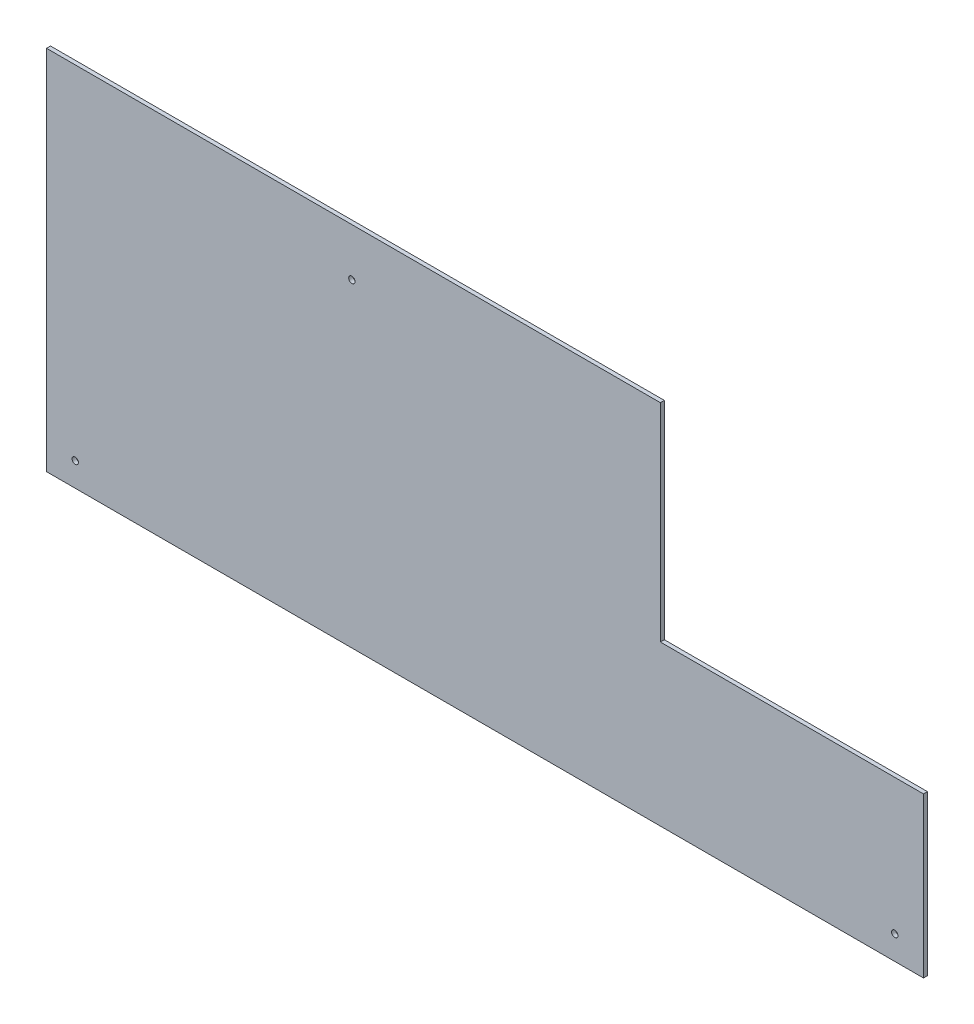
SolidWorks part; units mm, degrees
material "Acrilico (impatto medio-alto)"
ref_plane "Piano frontale" through (0, 0, 0) normal (0, 0, 1) x (1, 0, 0)
ref_plane "Piano superiore" through (0, 0, 0) normal (0, 1, 0) x (1, 0, 0)
ref_plane "Piano destro" through (0, 0, 0) normal (1, 0, 0) x (0, 0, -1)
sketch "Schizzo1" plane through (0, 0, 0) normal (0, 0, 1) x (1, 0, 0)
  line L1 (275, -115) -> (-275, -115)
  line L2 (275, -115) -> (275, 115)
  line L3 (275, 115) -> (-275, 115)
  line L4 (-275, -115) -> (-275, 115)
  line L5 (275, -115) -> (-275, 115) construction
  line L6 (275, 115) -> (-275, -115) construction
  point P4 (0, 0)
  dimension "D1" = 230
  dimension "D2" = 550
extrude "Estrusione-Estrusione1" add sketch "Schizzo1" along normal blind 2.5
sketch "Schizzo2" plane through (0, 0, 0) normal (0, 0, -1) x (-1, 0, 0)
  line L1 (-275, 115) -> (-110, 115)
  line L2 (-275, 115) -> (-275, -15)
  line L3 (-275, -15) -> (-110, -15)
  line L4 (-110, 115) -> (-110, -15)
  line L5 (-275, 115) -> (-110, -15) construction
  line L6 (-275, -15) -> (-110, 115) construction
  line L8 (-275, 115) -> (275, 115) construction
  line L9 (-275, -115) -> (-275, 115) construction
  point P4 (-192.5, 50)
  dimension "D1" = 130
  dimension "D3" = 165
extrude "Taglio-Estrusione1" cut sketch "Schizzo2" against normal blind 10
sketch "Schizzo3" plane through (0, 0, 2.5) normal (0, 0, 1) x (1, 0, 0)
  line L0 (-257, -100) -> (257, -100) construction
  line L1 (275, -115) -> (-275, -115) construction
  line L2 (275, 115) -> (275, -115) construction
  line L3 (-275, 115) -> (-275, -115) construction
  circle A0 centre (-83.5, 85) radius 2
  circle A1 centre (-257, -100) radius 2
  circle A2 centre (257, -100) radius 2
  dimension "D1" = 4
  dimension "D4" = 18
  dimension "D2" = 15
  dimension "D3" = 18
extrude "Taglio-Estrusione2" cut sketch "Schizzo3" against normal blind 10
